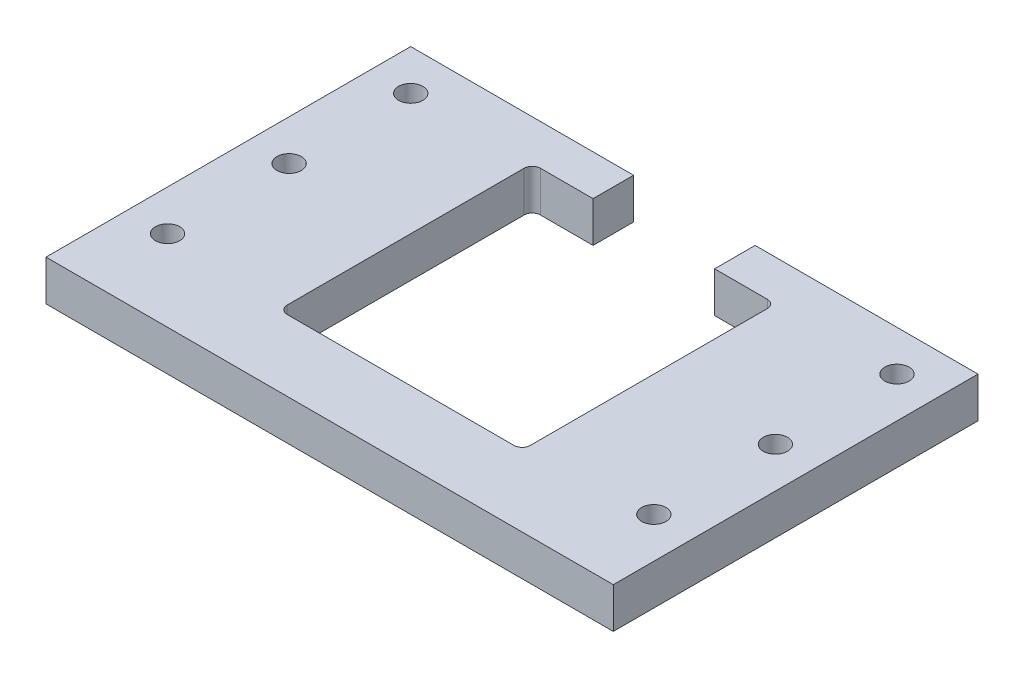
SolidWorks part; units mm, degrees
material "Balsa"
ref_plane "Front Plane" through (0, 0, 0) normal (0, 0, 1) x (1, 0, 0)
ref_plane "Top Plane" through (0, 0, 0) normal (0, 1, 0) x (1, 0, 0)
ref_plane "Right Plane" through (0, 0, 0) normal (1, 0, 0) x (0, 0, -1)
sketch "Sketch1" plane through (0, 0, 0) normal (0, 1, 0) x (1, 0, 0)
  line L0 (92.0676, 107.194) -> (161.9176, 107.194)
  line L1 (-15.8824, 107.194) -> (53.9676, 107.194)
  line L2 (-15.8824, 107.194) -> (-15.8824, -7.106)
  line L3 (-15.8824, -7.106) -> (161.9176, -7.106)
  line L4 (161.9176, 107.194) -> (161.9176, -7.106)
  line L8 (92.0676, 94.494) -> (92.0676, 107.194)
  line L9 (53.9676, 94.494) -> (37.4576, 94.494)
  line L10 (108.5776, 15.119) -> (37.4576, 15.119)
  line L11 (111.1176, 17.659) -> (111.1176, 91.954)
  line L12 (108.5776, 94.494) -> (92.0676, 94.494)
  line L13 (34.9176, 17.659) -> (34.9176, 91.954)
  line L14 (111.1176, 15.119) -> (110.3887, 15.8782) construction
  line L15 (111.1176, 94.494) -> (110.3887, 93.7348) construction
  line L16 (59.8248, 41.0641) -> (34.9176, 15.119) construction
  line L17 (73.0176, -7.106) -> (73.0176, 109.3999) construction
  line L18 (35.6464, 93.7348) -> (34.9176, 94.494) construction
  line L19 (53.9676, 94.494) -> (53.9676, 107.194)
  arc A1 (37.4576, 15.119) -> (34.9176, 17.659) centre (37.4576, 17.659) cw
  arc A2 (37.4576, 94.494) -> (34.9176, 91.954) centre (37.4576, 91.954) ccw
  arc A3 (111.1176, 91.954) -> (108.5776, 94.494) centre (108.5776, 91.954) ccw
  arc A4 (108.5776, 15.119) -> (111.1176, 17.659) centre (108.5776, 17.659) ccw
  circle A5 centre (-3.1824, 94.494) radius 3.81
  circle A6 centre (-3.1824, 56.394) radius 3.81
  circle A7 centre (-3.1824, 18.294) radius 3.81
  circle A8 centre (149.2176, 94.494) radius 3.81
  circle A9 centre (149.2176, 56.394) radius 3.81
  circle A10 centre (149.2176, 18.294) radius 3.81
  dimension "D3" = 12.7
  dimension "D8" = 2.54
  dimension "D5" = 7.62
  dimension "D1" = 177.8
  dimension "D2" = 114.3
  dimension "D4" = 50.8
  dimension "D6" = 76.2
  dimension "D7" = 79.375
  dimension "D9" = 12.7
  dimension "D10" = 12.7
  dimension "D12" = 38.1
  dimension "D11" = 3
extrude "Boss-Extrude1" add sketch "Sketch1" along normal blind 12.7
